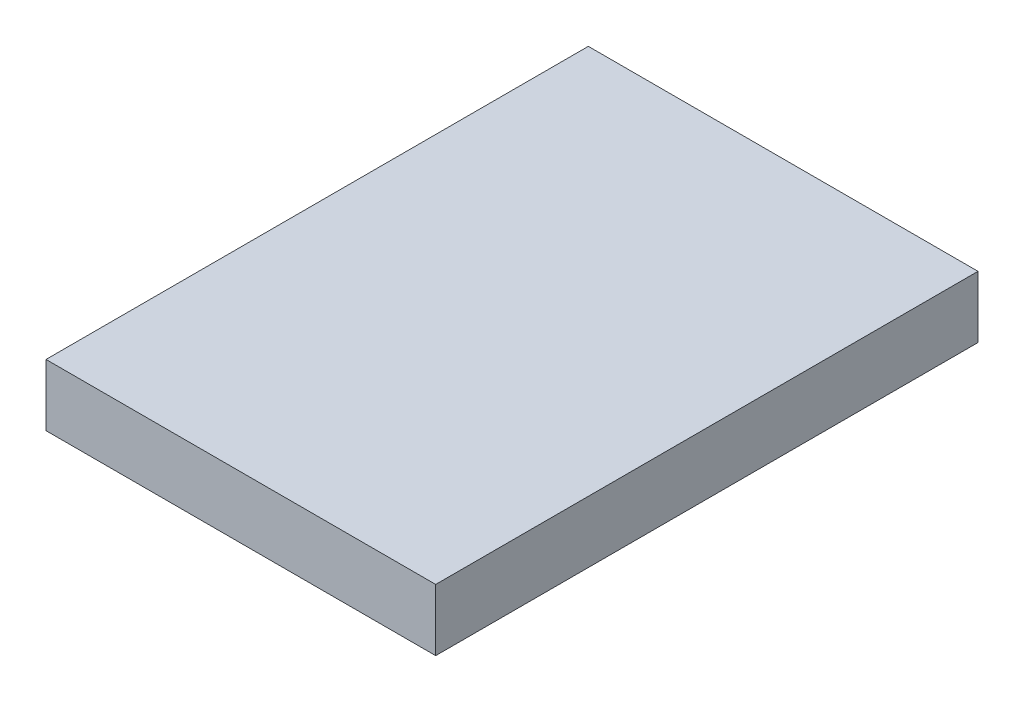
SolidWorks part; units mm, degrees
ref_plane "前视基准面" through (0, 0, 0) normal (0, 0, 1) x (1, 0, 0)
ref_plane "上视基准面" through (0, 0, 0) normal (0, 1, 0) x (1, 0, 0)
ref_plane "右视基准面" through (0, 0, 0) normal (1, 0, 0) x (0, 0, -1)
sketch "草图2" plane through (0, 0, 0) normal (0, 1, 0) x (1, 0, 0)
  line L1 (0, 0) -> (60, 0)
  line L2 (0, 0) -> (0, -83.5)
  line L3 (0, -83.5) -> (60, -83.5)
  line L4 (60, 0) -> (60, -83.5)
  dimension "D1" = 83.5
  dimension "D2" = 60
extrude "凸台-拉伸1" add sketch "草图2" along normal blind 9.5
